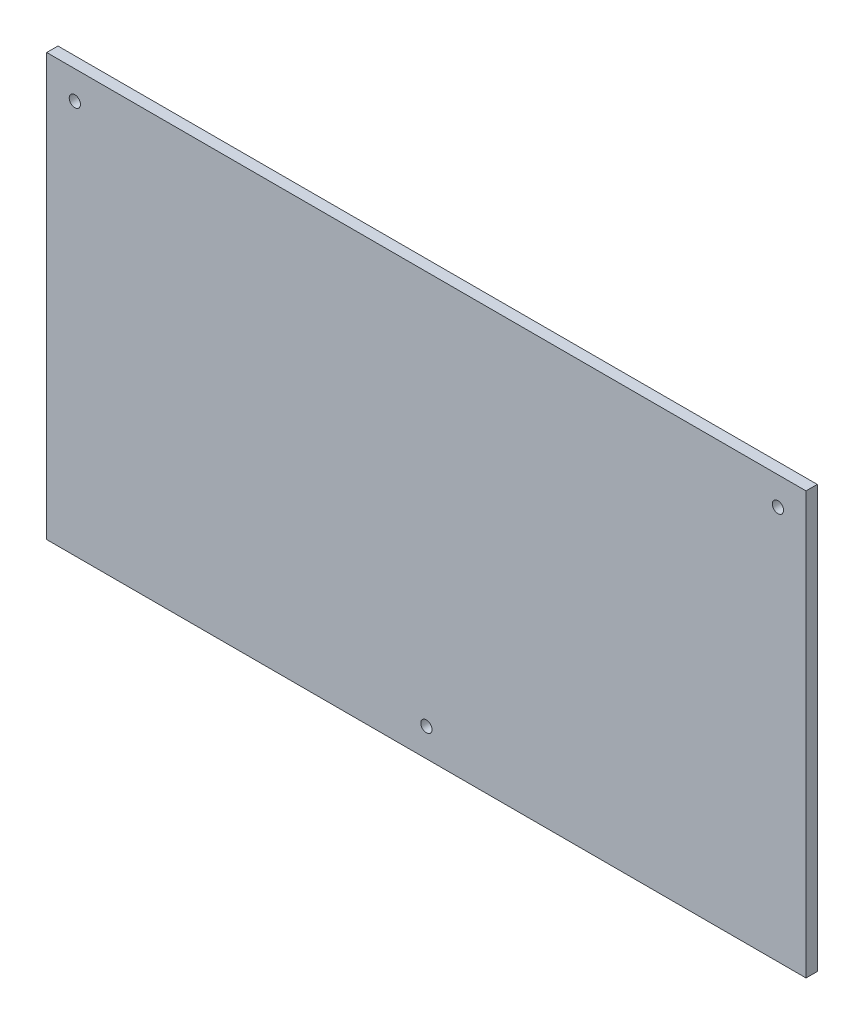
SolidWorks part; units mm, degrees
ref_plane "Front Plane" through (0, 0, 0) normal (0, 0, 1) x (1, 0, 0)
ref_plane "Top Plane" through (0, 0, 0) normal (0, 1, 0) x (1, 0, 0)
ref_plane "Right Plane" through (0, 0, 0) normal (1, 0, 0) x (0, 0, -1)
sketch "Sketch2" plane through (0, 0, 0) normal (0, 0, 1) x (1, 0, 0)
  line L0 (0, 0) -> (270, 0)
  line L1 (270, 0) -> (270, 150)
  line L2 (270, 150) -> (0, 150)
  line L3 (0, 150) -> (0, 0)
  line L4 (135, 0) -> (135, 10)
  circle A0 centre (10, 140) radius 2
  circle A1 centre (260, 140) radius 2
  circle A2 centre (135, 10) radius 2
  dimension "D6" = 4
  dimension "D7" = 4
  dimension "D8" = 4
  dimension "D3" = 10
  dimension "D4" = 10
  dimension "D5" = 10
  dimension "D11" = 130
  dimension "D1" = 270
  dimension "D2" = 150
  dimension "D9" = 10
  dimension "D10" = 10
extrude "Boss-Extrude1" add sketch "Sketch2" along normal blind 4
